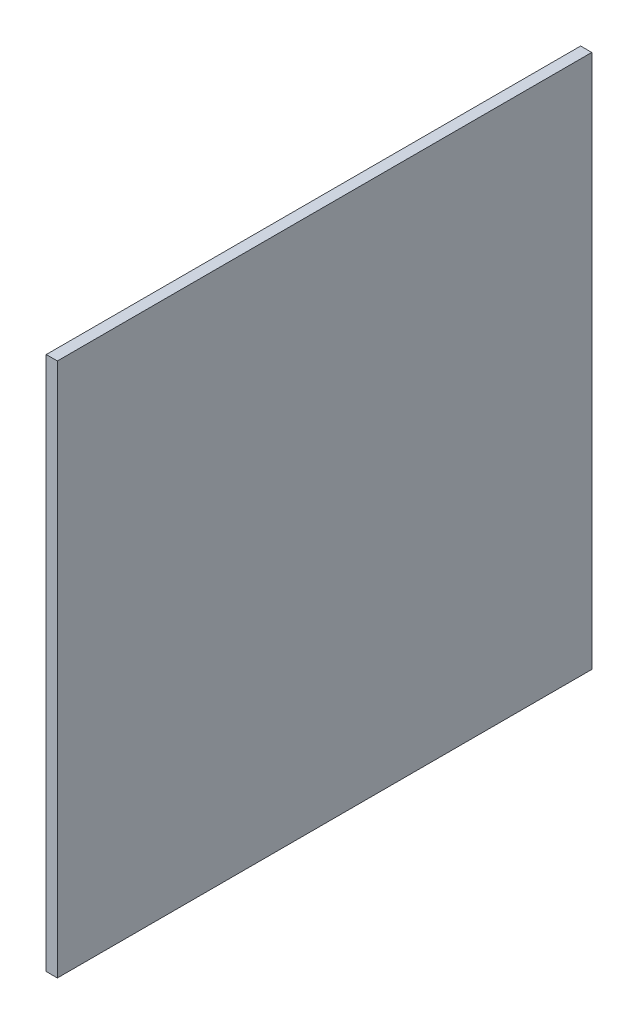
SolidWorks part; units mm, degrees
ref_plane "Front Plane" through (0, 0, 0) normal (0, 0, 1) x (1, 0, 0)
ref_plane "Top Plane" through (0, 0, 0) normal (0, 1, 0) x (1, 0, 0)
ref_plane "Right Plane" through (0, 0, 0) normal (1, 0, 0) x (0, 0, -1)
sketch "Sketch1" plane through (0, 0, 0) normal (1, 0, 0) x (0, 0, -1)
  line L1 (152.4, 152.4) -> (-152.4, 152.4)
  line L2 (152.4, 152.4) -> (152.4, -152.4)
  line L3 (152.4, -152.4) -> (-152.4, -152.4)
  line L4 (-152.4, 152.4) -> (-152.4, -152.4)
  line L5 (152.4, 152.4) -> (-152.4, -152.4) construction
  line L6 (152.4, -152.4) -> (-152.4, 152.4) construction
  point P0 (0, 0)
  dimension "D1" = 304.8
  dimension "D2" = 304.8
extrude "Boss-Extrude1" add sketch "Sketch1" along normal blind 6.35
